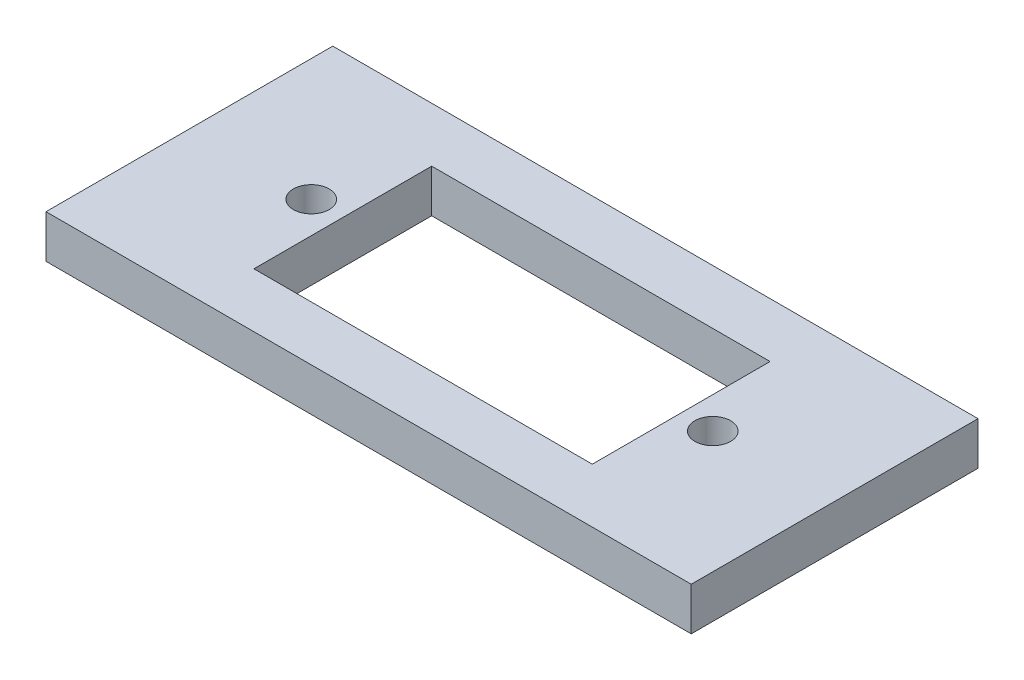
SolidWorks part; units mm, degrees
material "MDF"
ref_plane "Alzado" through (0, 0, 0) normal (0, 0, 1) x (1, 0, 0)
ref_plane "Planta" through (0, 0, 0) normal (0, 1, 0) x (1, 0, 0)
ref_plane "Vista lateral" through (0, 0, 0) normal (1, 0, 0) x (0, 0, -1)
sketch "Croquis1" plane through (0, 0, 0) normal (0, 1, 0) x (1, 0, 0)
  line L1 (-11.8, 6.2) -> (11.8, 6.2)
  line L2 (-11.8, 6.2) -> (-11.8, -6.2)
  line L3 (-11.8, -6.2) -> (11.8, -6.2)
  line L4 (11.8, 6.2) -> (11.8, -6.2)
  line L5 (-11.8, 6.2) -> (11.8, -6.2) construction
  line L6 (-11.8, -6.2) -> (11.8, 6.2) construction
  line L13 (-22.5, 10) -> (22.5, 10)
  line L14 (-22.5, 10) -> (-22.5, -10)
  line L15 (-22.5, -10) -> (22.5, -10)
  line L16 (22.5, 10) -> (22.5, -10)
  line L17 (-22.5, 10) -> (22.5, -10) construction
  line L18 (-22.5, -10) -> (22.5, 10) construction
  circle A0 centre (14, 0) radius 1.25
  circle A1 centre (-14, 0) radius 1.25
  point P0 (0, 0)
  point P14 (0, 0)
  dimension "D5" = 2.5
  dimension "D1" = 12.4
  dimension "D2" = 23.6
  dimension "D3" = 20
  dimension "D4" = 45
  dimension "D6" = 10
  dimension "D7" = 8.5
  dimension "D8" = 28
extrude "Saliente-Extruir1" add sketch "Croquis1" along normal blind 3
